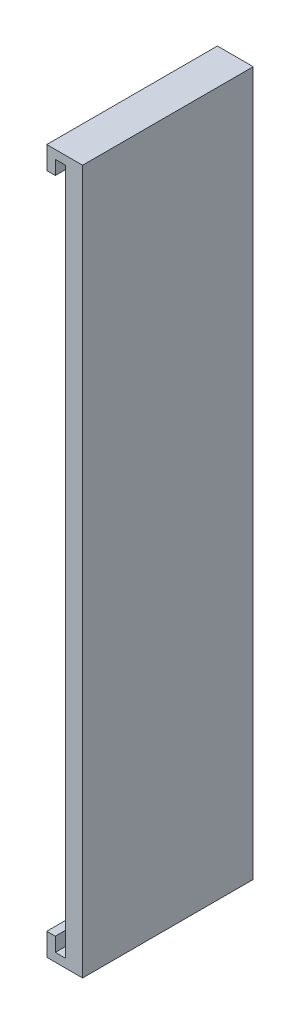
SolidWorks part; units mm, degrees
ref_plane "Front Plane" through (0, 0, 0) normal (1, 0, 0) x (0, 1, 0)
ref_plane "Top Plane" through (0, 0, 0) normal (0, 0, 1) x (0, 1, 0)
ref_plane "Right Plane" through (0, 0, 0) normal (0, 1, 0) x (-1, 0, 0)
sketch "Sketch1" plane through (0, 0, 0) normal (0, 0, 1) x (0, 1, 0)
  line L0 (-41.25, 1.6) -> (-38.6035, 1.6)
  line L9 (-40.25, -0.6) -> (40.25, -0.6)
  line L10 (-40.25, -0.6) -> (-40.25, 0.6)
  line L11 (-40.25, 0.6) -> (-38.6035, 0.6)
  line L12 (40.25, -0.6) -> (40.25, 0.6)
  line L13 (-40.25, -0.6) -> (40.25, 0.6) construction
  line L14 (-40.25, 0.6) -> (40.25, -0.6) construction
  line L15 (41.25, -2.6) -> (41.25, 1.6)
  line L17 (-41.25, -2.6) -> (-41.25, 1.6)
  line L18 (-38.6035, 1.6) -> (-38.6035, 0.6)
  line L19 (-41.25, -1.6) -> (41.25, -1.6) construction
  line L20 (-41.25, -2.6) -> (58.7943, -2.6)
  line L21 (-41.25, -1.6) -> (-41.25, 1.6) construction
  line L22 (41.25, -1.6) -> (41.25, 1.6) construction
  line L23 (0, 0) -> (0, 5.565) construction
  line L24 (38.6035, 1.6) -> (38.6035, 0.6)
  line L25 (38.6035, 1.6) -> (41.25, 1.6)
  line L26 (-41.25, 1.6) -> (41.25, 1.6) construction
  line L27 (38.6035, 0.6) -> (40.25, 0.6)
  line L28 (-38.6035, -0.5755) -> (-38.6035, -0.6)
  line L29 (-40.25, 0.6) -> (40.25, 0.6) construction
  point P0 (0, 0)
  dimension "D1" = 80.5
  dimension "D2" = 1.2
  dimension "D3" = 1.6465
  dimension "D4" = 1
  dimension "D5" = 2
extrude "Boss-Extrude1" add sketch "Sketch1" along normal blind 20 contours L24 L27 L12 L9 L10 L11 L18 L0 L17 L20 L15 L25
